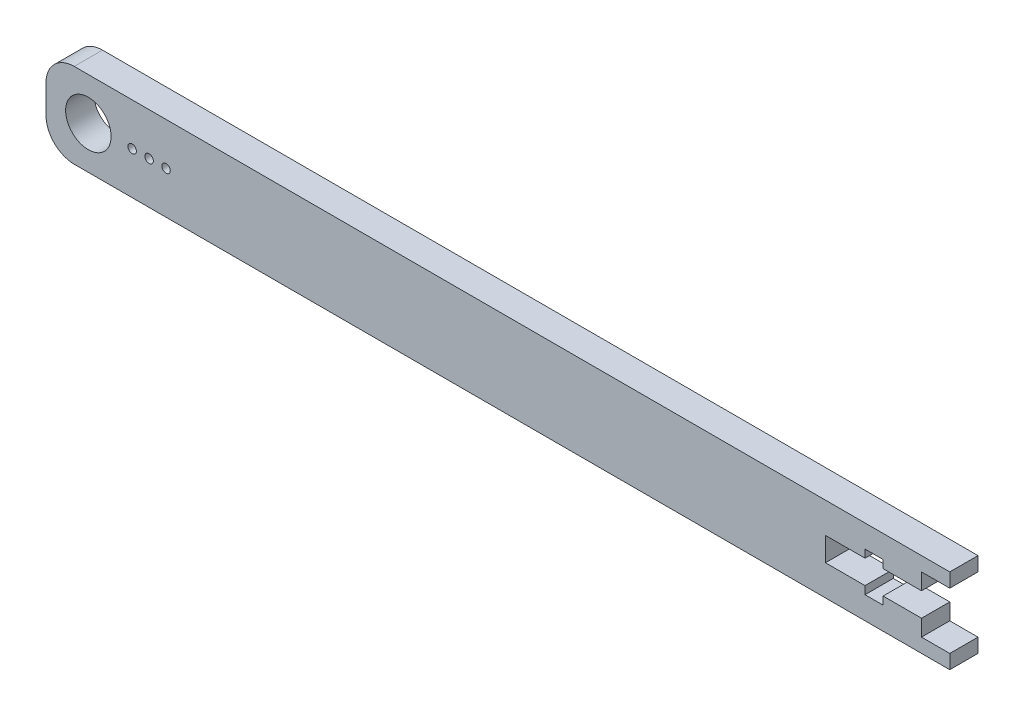
SolidWorks part; units mm, degrees
ref_plane "Front Plane" through (0, 0, 0) normal (0, 0, 1) x (1, 0, 0)
ref_plane "Top Plane" through (0, 0, 0) normal (0, 1, 0) x (1, 0, 0)
ref_plane "Right Plane" through (0, 0, 0) normal (1, 0, 0) x (0, 0, -1)
sketch "Sketch1" plane through (0, 0, 0) normal (0, 0, 1) x (1, 0, 0)
  line L5 (-215, 15) -> (-60, 15)
  line L6 (-220, 10) -> (-220, 5)
  line L7 (-215, 0) -> (-60, 0)
  line L8 (-55, 10) -> (-55, 5)
  line L9 (-65, 12.5) -> (-60, 12.5)
  line L10 (-65, 12.5) -> (-65, 2.5)
  line L11 (-65, 2.5) -> (-60, 2.5)
  line L12 (-60, 12.5) -> (-60, 2.5)
  arc A0 (-220, 5) -> (-215, 0) centre (-215, 5) ccw
  arc A1 (-215, 15) -> (-220, 10) centre (-215, 10) ccw
  arc A2 (-60, 0) -> (-55, 5) centre (-60, 5) ccw
  arc A3 (-60, 15) -> (-55, 10) centre (-60, 10) cw
  circle A4 centre (-212.5, 7.5) radius 4.025
  circle A5 centre (-204.75, 7.5) radius 0.75
  circle A6 centre (-201.75, 7.5) radius 0.75
  circle A7 centre (-198.75, 7.5) radius 0.75
  point P3 (-220, 0)
  point P11 (-220, 15)
  dimension "D3" = 5
  dimension "D4" = 8.05
  dimension "D6" = 7.5
  dimension "D7" = 5
  dimension "D8" = 2.5
  dimension "D9" = 5
  dimension "D11" = 1.5
  dimension "D12" = 7.75
  dimension "D13" = 1.5
  dimension "D14" = 1.5
  dimension "D1" = 10
  dimension "D2" = 15
  dimension "D5" = 7.5
  dimension "D10" = 155
  dimension "D15" = 10.75
  dimension "D16" = 13.75
extrude "Boss-Extrude1" add sketch "Sketch1" along normal blind 5
sketch "Sketch2" plane through (0, 0, 0) normal (0, 0, -1) x (-1, 0, 0)
  line L0 (65, 9.6) -> (71.8, 9.6)
  line L1 (65, 12.5) -> (65, 2.5) construction
  line L2 (71.8, 9.6) -> (71.8, 11)
  line L3 (71.8, 11) -> (75, 11)
  line L4 (75, 11) -> (75, 9.6)
  line L5 (75, 9.6) -> (82, 9.6)
  line L6 (82, 9.6) -> (82, 5.4)
  line L7 (82, 5.4) -> (75, 5.4)
  line L8 (75, 5.4) -> (75, 4)
  line L9 (75, 4) -> (71.8, 4)
  line L10 (71.8, 4) -> (71.8, 5.4)
  line L11 (71.8, 5.4) -> (65, 5.4)
  line L12 (65, 9.6) -> (65, 5.4)
  point P4 (65, 7.5)
  point P15 (82, 7.5)
  dimension "D1" = 6.8
  dimension "D2" = 17
  dimension "D3" = 3.2
  dimension "D4" = 3.2
  dimension "D5" = 6.8
  dimension "D6" = 4.2
  dimension "D7" = 7
extrude "Cut-Extrude1" cut sketch "Sketch2" against normal blind 10
sketch "Sketch3" plane through (0, 0, 0) normal (0, 0, -1) x (-1, 0, 0)
  line L0 (60, 15) -> (60, 0)
  line L4 (220, 5) -> (220, 10)
  line L5 (215, 15) -> (60, 15)
  line L6 (55, 10) -> (55, 5)
  line L7 (60, 0) -> (215, 0)
  line L10 (55, 10) -> (55, 5)
  arc A4 (215, 0) -> (220, 5) centre (215, 5) ccw
  arc A5 (220, 10) -> (215, 15) centre (215, 10) ccw
  arc A6 (60, 15) -> (55, 10) centre (60, 10) ccw
  arc A7 (55, 5) -> (60, 0) centre (60, 5) ccw
  arc A10 (60, 15) -> (55, 10) centre (60, 10) ccw
  arc A11 (55, 5) -> (60, 0) centre (60, 5) ccw
  dimension "D1" = 0
extrude "Cut-Extrude2" cut sketch "Sketch3" against normal blind 10
